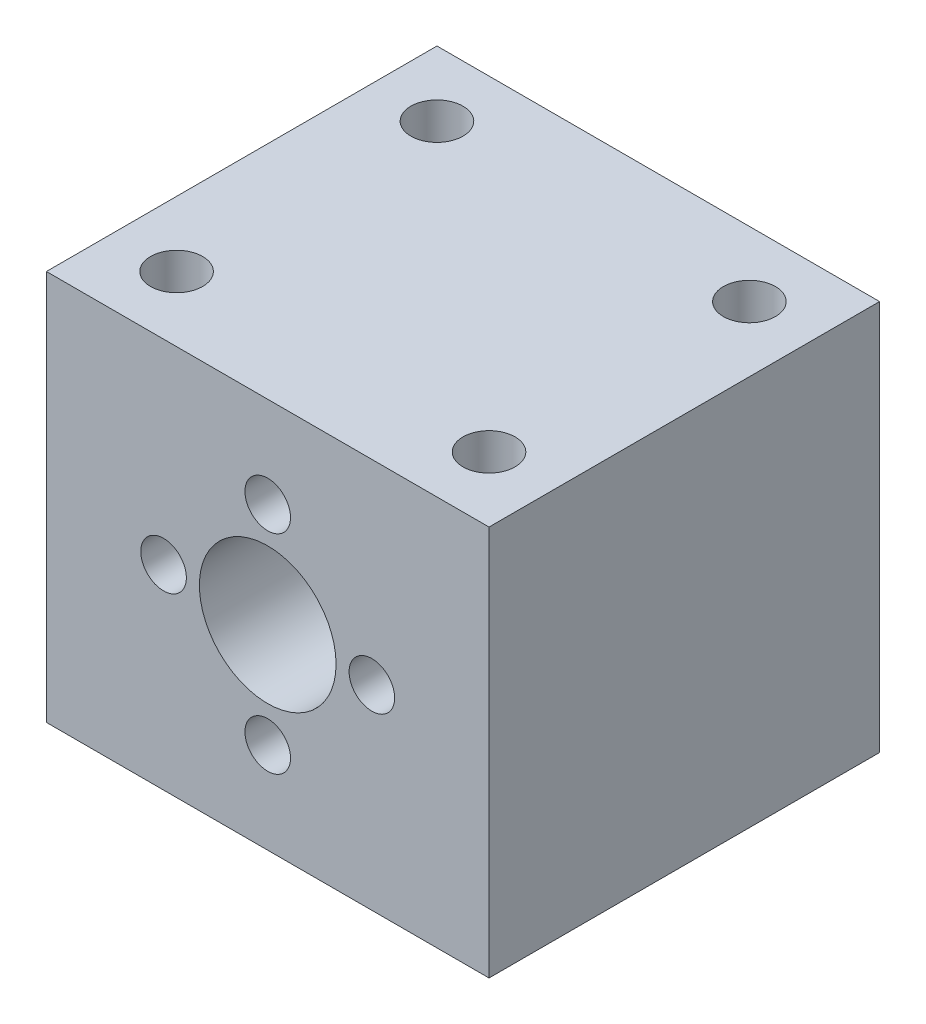
SolidWorks part; units mm, degrees
ref_plane "前视基准面" through (0, 0, 0) normal (0, 0, 1) x (1, 0, 0)
ref_plane "上视基准面" through (0, 0, 0) normal (0, 1, 0) x (1, 0, 0)
ref_plane "右视基准面" through (0, 0, 0) normal (1, 0, 0) x (0, 0, -1)
sketch "草图1" plane through (0, 0, 0) normal (0, 0, 1) x (1, 0, 0)
  line L1 (17, 15) -> (-17, 15)
  line L2 (17, 15) -> (17, -15)
  line L3 (17, -15) -> (-17, -15)
  line L4 (-17, 15) -> (-17, -15)
  circle A0 centre (0, 0) radius 5.25
  point P0 (0, 0)
  point P19 (0, 0)
  dimension "D1" = 34
  dimension "D2" = 30
extrude "凸台-拉伸1" add sketch "草图1" along normal blind 30
sketch "草图2" plane through (0, 0, 30) normal (0, 0, 1) x (1, 0, 0)
  circle A0 centre (-8, 0) radius 1.75
  circle A1 centre (0, 8) radius 1.75
  circle A2 centre (8, 0) radius 1.75
  circle A3 centre (0, -8) radius 1.75
  point P12 (0, 0)
  dimension "D1" = 8
  dimension "D2" = 4
extrude "切除-拉伸1" cut sketch "草图2" against normal blind 10
sketch "草图4" plane through (0, 15, 0) normal (0, 1, 0) x (1, 0, 0)
  line L0 (17, -30) -> (-17, -30) construction
  line L1 (17, -30) -> (17, 0) construction
  circle A0 centre (12, -25) radius 2
  circle A1 centre (-12, -25) radius 2
  circle A2 centre (-12, -5) radius 2
  circle A3 centre (12, -5) radius 2
  dimension "D1" = 24
  dimension "D2" = 24
  dimension "D3" = 20
  dimension "D4" = 5
  dimension "D5" = 5
  dimension "D6" = 5
extrude "切除-拉伸3" cut sketch "草图4" against normal blind 10
sketch "草图5" plane through (0, -15, 0) normal (0, -1, 0) x (-1, 0, 0)
  line L0 (17, -30) -> (-17, -30) construction
  line L1 (17, -30) -> (17, 0) construction
  circle A0 centre (1, -25) radius 1.5
  circle A2 centre (6, -25) radius 1.5
  dimension "D1" = 5
  dimension "D2" = 5
  dimension "D3" = 11
extrude "切除-拉伸4" cut sketch "草图5" against normal blind 5
